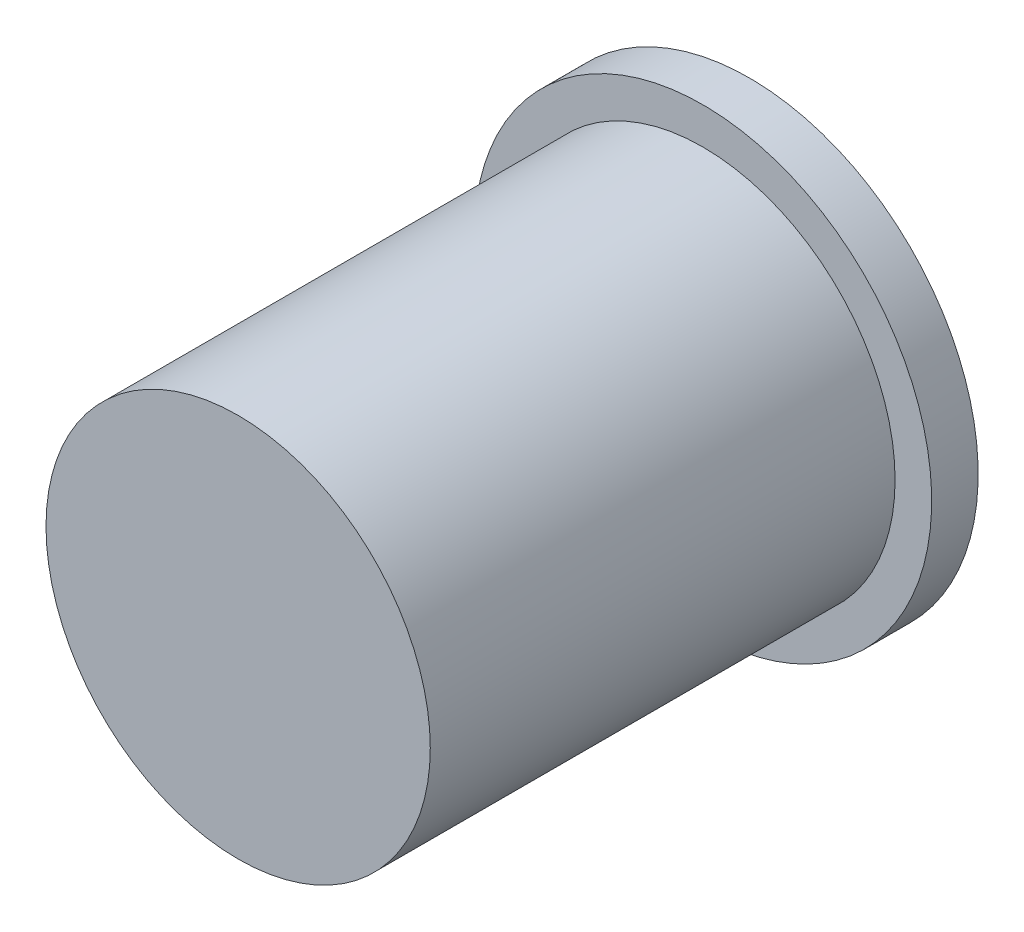
SolidWorks part; units mm, degrees
ref_plane "Front Plane" through (0, 0, 0) normal (0, 0, 1) x (1, 0, 0)
ref_plane "Top Plane" through (0, 0, 0) normal (0, 1, 0) x (1, 0, 0)
ref_plane "Right Plane" through (0, 0, 0) normal (1, 0, 0) x (0, 0, -1)
sketch "Sketch1" plane through (0, 0, 0) normal (0, 0, 1) x (1, 0, 0)
  circle A0 centre (0, 0) radius 10.5
  dimension "D1" = 21
extrude "Boss-Extrude2" add sketch "Sketch1" along normal blind 27.94 contours A0
sketch "Sketch2" plane through (0, 0, 0) normal (0, 0, -1) x (-1, 0, 0)
  circle A0 centre (0, 0) radius 12.5
  dimension "D1" = 25
extrude "Boss-Extrude3" add sketch "Sketch2" against normal blind 2.54
sketch "Sketch3" plane through (0, 0, 0) normal (0, 0, -1) x (-1, 0, 0)
  circle A0 centre (0, 0) radius 10
  dimension "D1" = 20
extrude "Cut-Extrude2" cut sketch "Sketch3" against normal blind 25.4 contours A0
